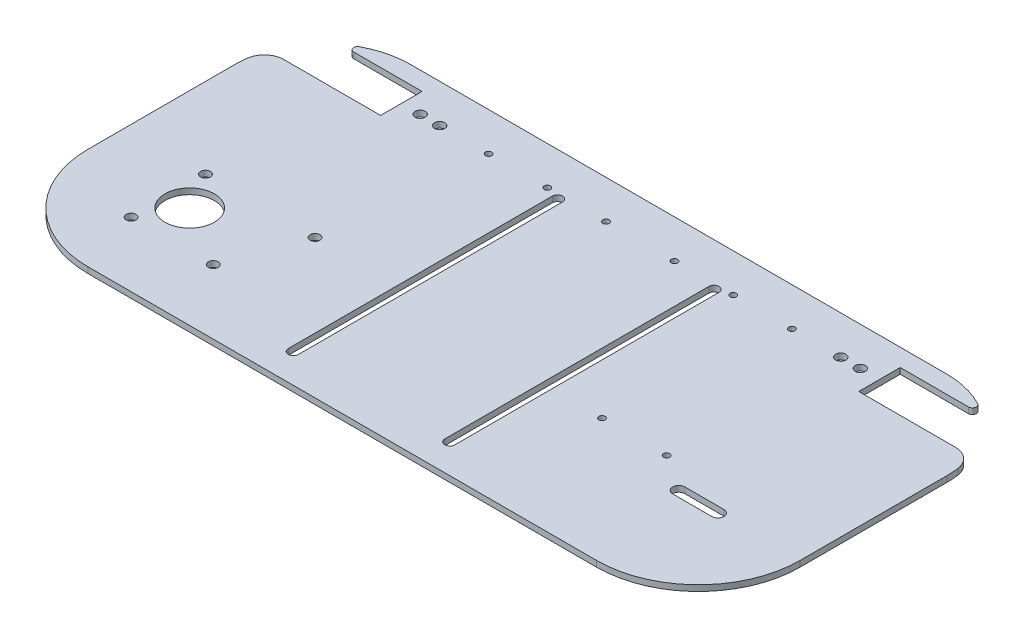
SolidWorks part; units mm, degrees
ref_plane "Front Plane" through (0, 0, 0) normal (0, 0, 1) x (1, 0, 0)
ref_plane "Top Plane" through (0, 0, 0) normal (0, 1, 0) x (1, 0, 0)
ref_plane "Right Plane" through (0, 0, 0) normal (1, 0, 0) x (0, 0, -1)
sketch "Sketch1" plane through (0, 0, 0) normal (0, 1, 0) x (1, 0, 0)
  line L0 (0, 0) -> (260, 0) construction
  line L5 (0, 52) -> (260, 52)
  line L6 (0, -52) -> (260, -52)
  line L7 (270, 0) -> (250, 0) construction
  line L8 (270, -3.1) -> (250, -3.1)
  line L9 (270, 3.1) -> (250, 3.1)
  line L11 (-52, 0) -> (312, 0) construction
  line L12 (-52, 0) -> (-52, 120)
  line L13 (-52, 120) -> (312, 120)
  line L14 (312, 0) -> (312, 120)
  arc A0 (0, 52) -> (0, -52) centre (0, 0) ccw
  arc A1 (260, -52) -> (260, 52) centre (260, 0) ccw
  circle A2 centre (0, 0) radius 3.1
  arc A4 (270, -3.1) -> (270, 3.1) centre (270, 0) ccw
  arc A5 (250, 3.1) -> (250, -3.1) centre (250, 0) ccw
  point P2 (130, 0)
  point P12 (260, 0)
  dimension "D2" = 52
  dimension "D3" = 6.2
  dimension "D1" = 260
  dimension "D4" = 20
  dimension "D5" = 120
  dimension "D6" = 270
extrude "Boss-Extrude1" add sketch "Sketch1" along normal blind 3 contours L6 A1 L5 A0 A5 L9 A4 L8 A2 | A1 L14 L13 L12 A0 L5
sketch "Sketch2" plane through (0, 3, 0) normal (0, 1, 0) x (1, 0, 0)
  line L0 (-52, 105) -> (312, 105) construction
  line L1 (-52, 0) -> (-52, 120) construction
  line L2 (312, 0) -> (312, 120) construction
  line L3 (-52, 120) -> (312, 120) construction
  line L4 (130, 120) -> (130, -52) construction
  line L5 (0, -52) -> (260, -52) construction
  line L6 (90, 120) -> (90, -52) construction
  line L7 (170, 120) -> (170, -52) construction
  line L11 (-36.5377, -37) -> (296.5377, -37) construction
  line L12 (90, -37) -> (90, 98) construction
  line L13 (87.4, -37) -> (87.4, 98)
  line L14 (92.6, -37) -> (92.6, 98)
  line L15 (170, -37) -> (170, 98) construction
  line L16 (172.6, -37) -> (172.6, 98)
  line L17 (167.4, -37) -> (167.4, 98)
  arc A2 (-52, 0) -> (0, -52) centre (0, 0) ccw construction
  arc A3 (260, -52) -> (312, 0) centre (260, 0) ccw construction
  arc A4 (87.4, -37) -> (92.6, -37) centre (90, -37) ccw
  arc A5 (92.6, 98) -> (87.4, 98) centre (90, 98) ccw
  arc A6 (172.6, -37) -> (167.4, -37) centre (170, -37) cw
  arc A7 (167.4, 98) -> (172.6, 98) centre (170, 98) cw
  point P33 (90, 30.5)
  point P40 (170, 30.5)
  dimension "D4" = 2.6
  dimension "D1" = 15
  dimension "D2" = 40
  dimension "D3" = 40
  dimension "D6" = 15
  dimension "D7" = 135
extrude "Cut-Extrude1" cut sketch "Sketch2" against normal through all
fillet "Fillet1" radius 45 2 edges at (312, 1.5, -120) (-52, 1.5, -120)
sketch "Sketch3" plane through (0, 3, 0) normal (0, 1, 0) x (1, 0, 0)
  circle A0 centre (0, 0) radius 12.6
  dimension "D1" = 25.2
extrude "Cut-Extrude2" cut sketch "Sketch3" against normal through all
sketch "Sketch4" plane through (0, 3, 0) normal (0, 1, 0) x (1, 0, 0)
  circle A0 centre (-10.9389, 19) radius 2.5
  circle A1 centre (45.07, 19) radius 2.5
  circle A2 centre (31.0611, -19) radius 2.5
  circle A3 centre (-10.9389, -19) radius 2.5
  circle A4 centre (-10.9389, 19) radius 2.5 construction
  circle A5 centre (-10.9389, -19) radius 2.5 construction
  circle A6 centre (31.0611, -19) radius 2.5 construction
  circle A7 centre (45.07, 19) radius 2.5 construction
extrude "Cut-Extrude3" cut sketch "Sketch4" against normal through all
sketch "Sketch5" plane through (0, 3, 0) normal (0, 1, 0) x (1, 0, 0)
  line L0 (260, -52) -> (260, 120) construction
  line L1 (-7, 120) -> (267, 120) construction
  line L2 (-7.6, 92.8) -> (-52, 92.8)
  line L3 (0, -52) -> (260, -52) construction
  line L4 (0, -52) -> (0, 120) construction
  line L5 (-7.6, 108) -> (7.6, 108)
  line L6 (-7.6, 108) -> (-7.6, 92.8)
  line L7 (-7.6, 92.8) -> (7.6, 92.8)
  line L8 (7.6, 108) -> (7.6, 92.8)
  line L9 (252.4, 108) -> (267.6, 108)
  line L10 (252.4, 108) -> (252.4, 92.8)
  line L11 (252.4, 92.8) -> (267.6, 92.8)
  line L12 (267.6, 108) -> (267.6, 92.8)
  line L13 (-7.6, 92.8) -> (-7.6, 108)
  line L14 (-7.6, 108) -> (-52, 108)
  line L15 (-52, 92.8) -> (-52, 108)
  line L16 (7.6, 92.8) -> (22.6, 92.8)
  line L17 (7.6, 92.8) -> (7.6, 108)
  line L18 (7.6, 108) -> (22.6, 108)
  line L19 (22.6, 92.8) -> (22.6, 108)
  line L20 (-52, 108) -> (22.6, 108)
  line L21 (-52, 108) -> (-52, 111)
  line L22 (-52, 111) -> (22.6, 111)
  line L23 (22.6, 108) -> (22.6, 111)
  line L24 (-52, 92.8) -> (22.6, 92.8)
  line L25 (-52, 92.8) -> (-52, 89.8)
  line L26 (-52, 89.8) -> (22.6, 89.8)
  line L27 (22.6, 92.8) -> (22.6, 89.8)
  line L28 (-52, 0) -> (-52, 75) construction
  line L29 (130, 120) -> (130, -52) construction
  line L30 (312, 92.8) -> (312, 108)
  line L31 (312, 92.8) -> (312, 89.8)
  line L32 (312, 89.8) -> (237.4, 89.8)
  line L33 (237.4, 92.8) -> (237.4, 89.8)
  line L34 (312, 92.8) -> (237.4, 92.8)
  line L35 (252.4, 92.8) -> (252.4, 108)
  line L36 (252.4, 108) -> (237.4, 108)
  line L37 (237.4, 92.8) -> (237.4, 108)
  line L38 (252.4, 92.8) -> (237.4, 92.8)
  line L39 (312, 108) -> (312, 111)
  line L40 (312, 111) -> (237.4, 111)
  line L41 (237.4, 108) -> (237.4, 111)
  line L42 (312, 108) -> (237.4, 108)
  line L43 (7.8, 111) -> (7.8, 89.8)
  line L44 (252.2, 111) -> (252.2, 89.8)
  arc A0 (260, -52) -> (312, 0) centre (260, 0) ccw construction
  arc A1 (-52, 0) -> (0, -52) centre (0, 0) ccw construction
  point P24 (0, 108)
  point P25 (260, 108)
  arc M25 (312, 75) -> (267, 120) centre (267, 75) ccw
  arc M27 (-7, 120) -> (-52, 75) centre (-7, 75) ccw
  dimension "D1" = 15.2
  dimension "D2" = 12
  dimension "D3" = 3
  dimension "D4" = 15
  dimension "D5" = 0.2
  dimension "D6" = 0.2
extrude "Cut-Extrude4" cut sketch "Sketch5" against normal through all contours L22 L21 L14 M27 | L43 L22 L14 L5 L18 M27 | L6 L14 L2 M27 | L43 L16 L7 L2 L26 M27 | L15 L2 L14 M27 | L25 L26 L2 M27 | L8 L5 L6 L7 | L43 L18 L8 L16 | L40 L44 L36 L9 L42 M25 | L12 L9 L10 L11 | L36 L44 L34 L10 | L34 L44 L32 L11 M25 | L42 L12 L34 M25 | L42 L39 L40 M25 | L30 L42 L34 M25 | L31 L34 L32 M25
sketch "Sketch10" plane through (0, 3, 0) normal (0, 1, 0) x (1, 0, 0)
  circle A0 centre (17.4, 100.4) radius 2.6
  circle A1 centre (27.4, 100.4) radius 2.6
  circle A2 centre (242.4, 100.4) radius 2.6
  circle A3 centre (232.4, 100.4) radius 2.6
  circle A4 centre (207.4, 100.4) radius 1.6
  circle A5 centre (177.4, 100.4) radius 1.6
  circle A6 centre (147.4, 100.4) radius 1.6
  circle A7 centre (112.4, 100.4) radius 1.6
  circle A8 centre (52.4, 100.4) radius 1.6
  circle A9 centre (82.4, 100.4) radius 1.6
  dimension "D1" = 5.2
  dimension "D2" = 3.2
extrude "Cut-Extrude8" cut sketch "Sketch10" against normal through all
fillet "Fillet2" radius 10 2 edges at (309.4966, 1.5, -89.8) (-49.4966, 1.5, -89.8)
fillet "Fillet3" radius 2 2 edges at (-34, 1.5, -111) (294, 1.5, -111)
sketch "Sketch11" plane through (0, 0, 0) normal (0, -1, 0) x (1, 0, 0)
  circle A0 centre (231.4, -12.4) radius 1.6
  circle A1 centre (198.4, -12.4) radius 1.6
  point P5 (231.4, -12.4)
  dimension "D1" = 3.2
extrude "Cut-Extrude9" cut sketch "Sketch11" against normal through all
